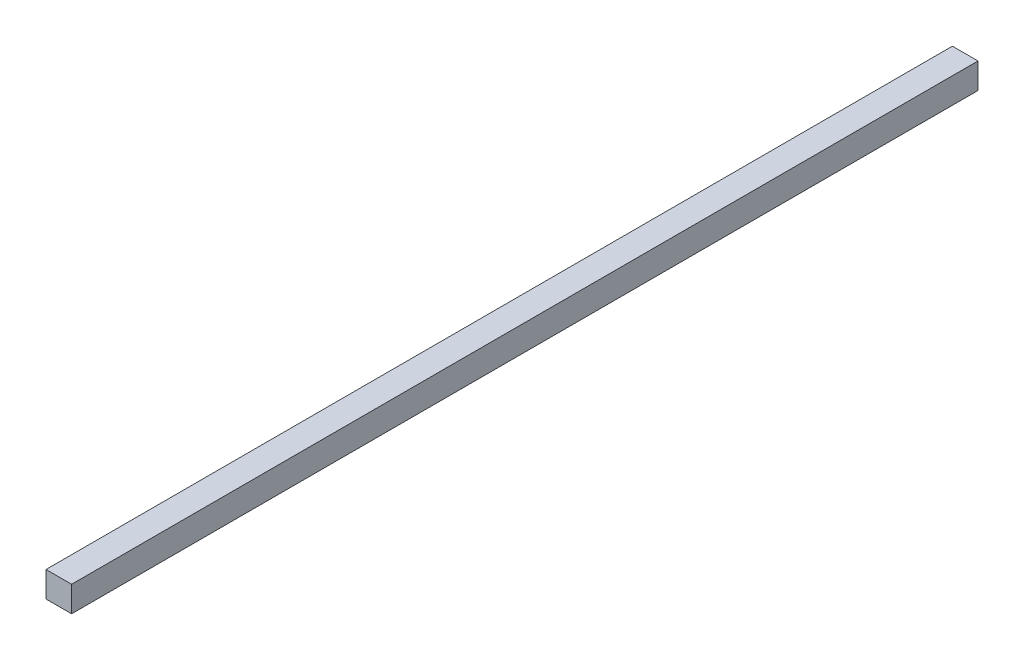
SolidWorks part; units mm, degrees
ref_plane "Front Plane" through (0, 0, 0) normal (0, 0, 1) x (1, 0, 0)
ref_plane "Top Plane" through (0, 0, 0) normal (0, 1, 0) x (1, 0, 0)
ref_plane "Right Plane" through (0, 0, 0) normal (1, 0, 0) x (0, 0, -1)
sketch "Sketch2" plane through (0, 0, 0) normal (0, 0, 1) x (1, 0, 0)
  line L1 (0, 0) -> (6.35, 0)
  line L2 (0, 0) -> (0, 6.35)
  line L3 (0, 6.35) -> (6.35, 6.35)
  line L4 (6.35, 0) -> (6.35, 6.35)
  dimension "D1" = 6.35
  dimension "D2" = 6.35
extrude "Boss-Extrude1" add sketch "Sketch2" along normal blind 224.79
